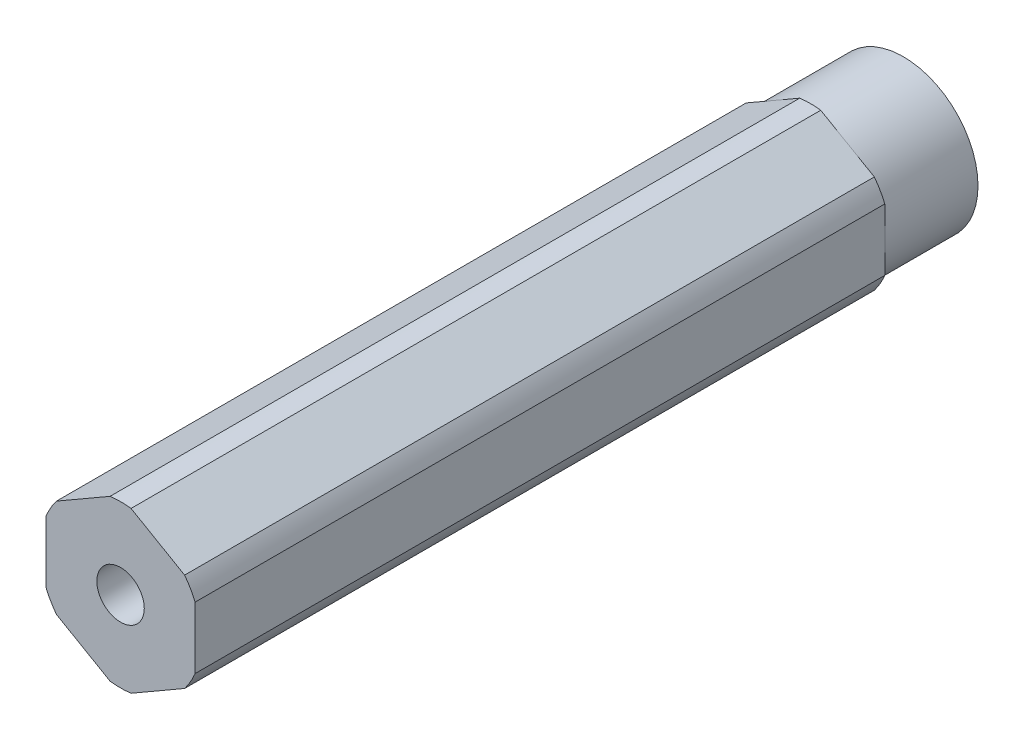
SolidWorks part; units mm, degrees
material "7075-T6 (SN)"
ref_plane "Front Plane" through (0, 0, 0) normal (0, 0, 1) x (1, 0, 0)
ref_plane "Top Plane" through (0, 0, 0) normal (0, 1, 0) x (1, 0, 0)
ref_plane "Right Plane" through (0, 0, 0) normal (1, 0, 0) x (0, 0, -1)
sketch "Sketch1" plane through (0, 0, 0) normal (0, 0, 1) x (1, 0, 0)
  line L0 (0, 7.3323) -> (-0.893, 6.8168) construction
  line L1 (-0.893, 6.8168) -> (-5.457, 4.1818)
  line L2 (-6.35, 2.635) -> (-6.35, -2.635)
  line L3 (-5.457, -4.1818) -> (-0.893, -6.8168)
  line L4 (0.893, -6.8168) -> (5.457, -4.1818)
  line L5 (6.35, -2.635) -> (6.35, 2.635)
  line L6 (5.457, 4.1818) -> (0.893, 6.8168)
  line L7 (0.893, 6.8168) -> (0, 7.3323) construction
  circle A0 centre (0, 0) radius 6.35 construction
  arc A2 (-6.35, -2.635) -> (-5.457, -4.1818) centre (0, 0) ccw
  arc A3 (-5.457, 4.1818) -> (-6.35, 2.635) centre (0, 0) ccw
  arc A4 (0.893, 6.8168) -> (-0.893, 6.8168) centre (0, 0) ccw
  arc A5 (-0.893, -6.8168) -> (0.893, -6.8168) centre (0, 0) ccw
  arc A6 (5.457, -4.1818) -> (6.35, -2.635) centre (0, 0) ccw
  arc A7 (6.35, 2.635) -> (5.457, 4.1818) centre (0, 0) ccw
  dimension "D1" = 12.7
  dimension "D2" = 13.75
extrude "Boss-Extrude1" add sketch "Sketch1" along normal mid plane 66.675
sketch "Sketch3" plane through (0, 0, 33.3375) normal (0, 0, 1) x (1, 0, 0)
  circle A0 centre (0, 0) radius 2.0193
  dimension "D1" = 4.0386
extrude "Cut-Extrude1" cut sketch "Sketch3" against normal through all
sketch "Sketch8" plane through (0, 0, -33.3375) normal (0, 0, -1) x (-1, 0, 0)
  circle A0 centre (0, 0) radius 6.35
  circle A1 centre (0, 0) radius 6.875
  arc A2 (0.893, 6.8168) -> (-0.893, 6.8168) centre (0, 0) ccw construction
  dimension "D1" = 12.7
extrude "Cut-Extrude3" cut sketch "Sketch8" against normal blind 7.9375
hole_wizard "#10-32 Tapped Hole1" positions "3DSketch1" profile "Sketch9" tap size "#10-32" standard "ANSI Inch"
sketch3d "3DSketch1"
  circle A0 centre (0, 0, 33.3375) radius 2.0193 construction
  circle A1 centre (0, 0, -33.3375) radius 2.0193 construction
  point P0 (0, 0, -33.3375)
  point P2 (0, 0, 33.3375)
  point P7 (0, 0, 35.3568)
  point P11 (0, 0, -31.3182)
sketch "Sketch9" plane through (0, 0, -33.3375) normal (1, 0, 0) x (0, 1, 0)
  line L0 (0, 0) -> (0, 13.2428)
  line L1 (0, 13.2428) -> (2.0193, 12.0294)
  line L2 (2.0193, 12.0294) -> (2.0193, 0)
  line L5 (2.0193, 0) -> (0, 0)
  line L10 (0, 13.2428) -> (-2.0193, 12.0294) construction
  line L11 (0, -6.35) -> (0, 107.95) construction
  dimension "Tap Drill Dia." = 4.0386
  dimension "Tap Drill Depth" = 12.0294
  dimension "Drill Angle" = 118
cosmetic thread "Hole Thread1" parameters "D1"=9.652, "D2"=4.826
cosmetic thread "Hole Thread2" parameters "D1"=9.652, "D2"=4.826
